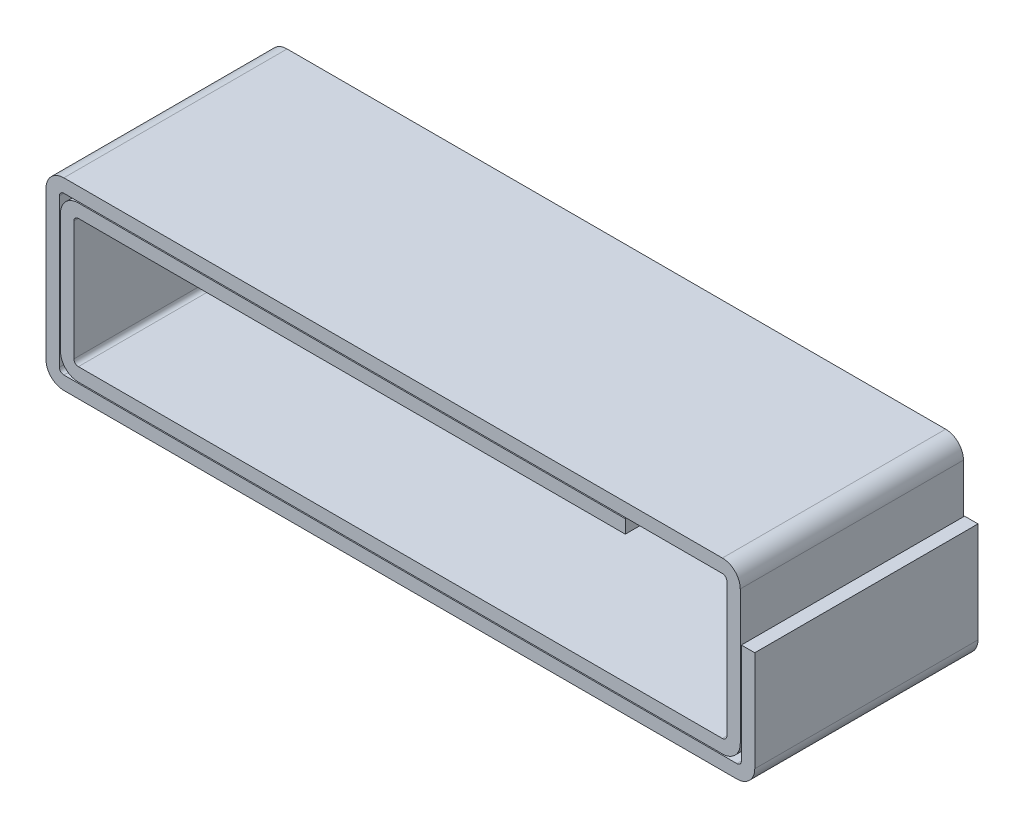
SolidWorks part; units mm, degrees
material "Velcro, Nylon"
ref_plane "Front Plane" through (0, 0, 0) normal (0, 0, 1) x (1, 0, 0)
ref_plane "Top Plane" through (0, 0, 0) normal (0, 1, 0) x (1, 0, 0)
ref_plane "Right Plane" through (0, 0, 0) normal (1, 0, 0) x (0, 0, -1)
sketch "Sketch1" plane through (0, 0, 0) normal (0, 0, 1) x (1, 0, 0)
  line L0 (-29.85, 11.7) -> (-29.85, 1) construction
  line L5 (-28.85, 0) -> (28.85, 0) construction
  line L6 (29.85, 1) -> (29.85, 13) construction
  line L7 (-28.85, 12.7) -> (20.15, 12.7) construction
  line L8 (28.85, 14) -> (-30.15, 14) construction
  line L9 (-31.15, 13) -> (-31.15, -0.3) construction
  line L10 (-30.15, -1.3) -> (30.15, -1.3) construction
  line L11 (31.15, -0.3) -> (31.15, 8.7) construction
  line L12 (-28.85, 13.3) -> (20.15, 13.3)
  line L13 (-30.45, 11.7) -> (-30.45, 1)
  line L14 (-28.85, -0.6) -> (28.85, -0.6)
  line L15 (30.45, 1) -> (30.45, 13)
  line L16 (28.85, 14.6) -> (-30.15, 14.6)
  line L17 (-31.75, 13) -> (-31.75, -0.3)
  line L18 (-30.15, -1.9) -> (30.15, -1.9)
  line L19 (31.75, -0.3) -> (31.75, 8.7)
  line L20 (-28.85, 12.1) -> (20.15, 12.1)
  line L21 (-29.25, 11.7) -> (-29.25, 1)
  line L22 (-28.85, 0.6) -> (28.85, 0.6)
  line L23 (29.25, 1) -> (29.25, 13)
  line L24 (28.85, 13.4) -> (-30.15, 13.4)
  line L25 (-30.55, 13) -> (-30.55, -0.3)
  line L26 (-30.15, -0.7) -> (30.15, -0.7)
  line L27 (30.55, -0.3) -> (30.55, 8.7)
  line L28 (20.15, 13.3) -> (20.15, 12.1)
  line L29 (30.55, 8.7) -> (31.75, 8.7)
  arc A0 (29.85, 13) -> (28.85, 14) centre (28.85, 13) ccw construction
  arc A1 (28.85, 0) -> (29.85, 1) centre (28.85, 1) ccw construction
  arc A2 (-29.85, 1) -> (-28.85, 0) centre (-28.85, 1) ccw construction
  arc A3 (-31.15, -0.3) -> (-30.15, -1.3) centre (-30.15, -0.3) ccw construction
  arc A4 (-30.15, 14) -> (-31.15, 13) centre (-30.15, 13) ccw construction
  arc A5 (-29.85, 11.7) -> (-28.85, 12.7) centre (-28.85, 11.7) cw construction
  arc A6 (30.15, -1.3) -> (31.15, -0.3) centre (30.15, -0.3) ccw construction
  arc A7 (-30.45, 11.7) -> (-28.85, 13.3) centre (-28.85, 11.7) cw
  arc A8 (-30.45, 1) -> (-28.85, -0.6) centre (-28.85, 1) ccw
  arc A9 (28.85, -0.6) -> (30.45, 1) centre (28.85, 1) ccw
  arc A10 (30.45, 13) -> (28.85, 14.6) centre (28.85, 13) ccw
  arc A11 (-30.15, 14.6) -> (-31.75, 13) centre (-30.15, 13) ccw
  arc A12 (-31.75, -0.3) -> (-30.15, -1.9) centre (-30.15, -0.3) ccw
  arc A13 (30.15, -1.9) -> (31.75, -0.3) centre (30.15, -0.3) ccw
  arc A14 (-29.25, 11.7) -> (-28.85, 12.1) centre (-28.85, 11.7) cw
  arc A15 (-29.25, 1) -> (-28.85, 0.6) centre (-28.85, 1) ccw
  arc A16 (28.85, 0.6) -> (29.25, 1) centre (28.85, 1) ccw
  arc A17 (29.25, 13) -> (28.85, 13.4) centre (28.85, 13) ccw
  arc A18 (-30.15, 13.4) -> (-30.55, 13) centre (-30.15, 13) ccw
  arc A19 (-30.55, -0.3) -> (-30.15, -0.7) centre (-30.15, -0.3) ccw
  arc A20 (30.15, -0.7) -> (30.55, -0.3) centre (30.15, -0.3) ccw
  point P21 (0, 0)
  dimension "D3" = 1
  dimension "D9" = 1
  dimension "D1" = 1.3
  dimension "D2" = 1.3
  dimension "D4" = 59
  dimension "D5" = 12
  dimension "D6" = 49
  dimension "D7" = 10.7
  dimension "D8" = 1.3
  dimension "D10" = 9
  dimension "D11" = 0.6
  dimension "D12" = 0.6
extrude "Boss-Extrude2" add sketch "Sketch1" along normal mid plane 20 contours L16 A11 L17 A12 L18 A13 L19 L29 L27 A20 L26 A19 L25 A18 L24 A17 L23 A16 L22 A15 L21 A14 L20 L28 L12 A7 L13 A8 L14 A9 L15 A10
